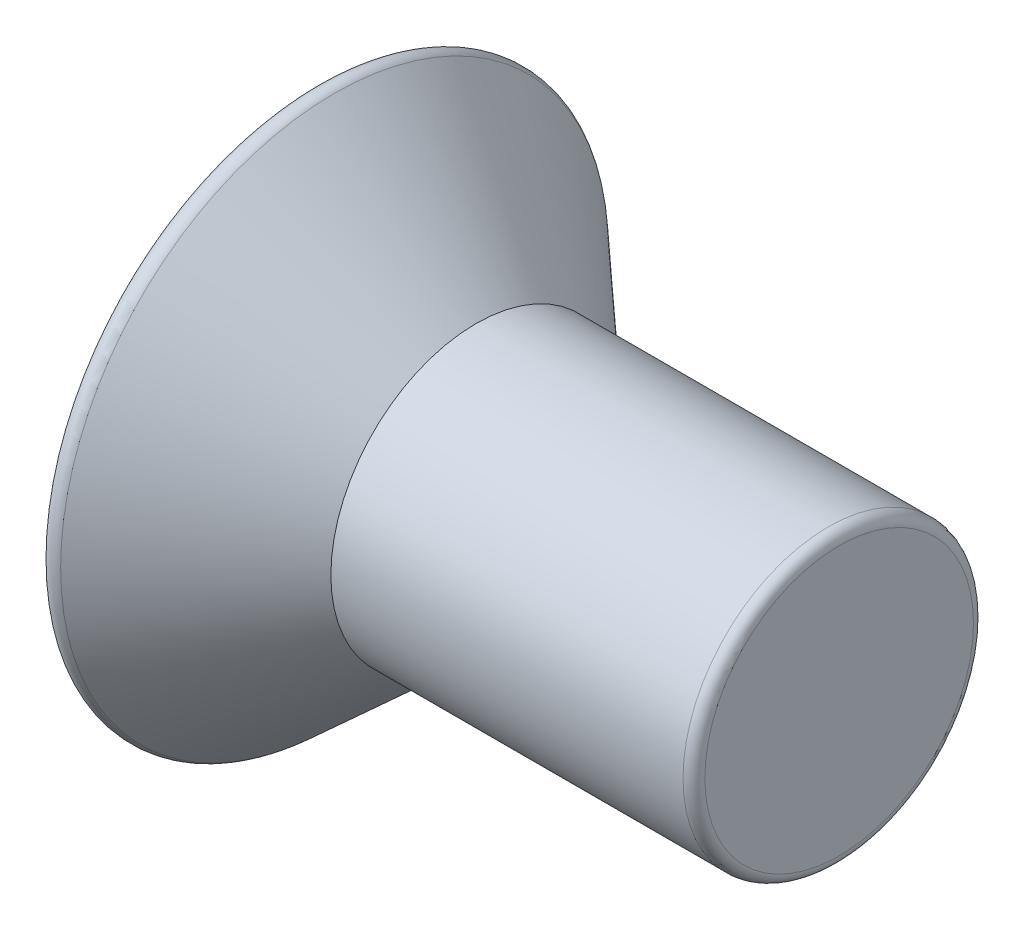
SolidWorks part; units mm, degrees
material "1.0044 (S275JR)"
ref_plane "Ön Düzlem" through (0, 0, 0) normal (0, 0, 1) x (1, 0, 0)
ref_plane "Üst Düzlem" through (0, 0, 0) normal (0, 1, 0) x (1, 0, 0)
ref_plane "Sağ Düzlem" through (0, 0, 0) normal (1, 0, 0) x (0, 0, -1)
sketch "Çizim1" plane through (0, 0, 0) normal (0, 0, 1) x (1, 0, 0)
  line L0 (0, 0) -> (0, 4)
  line L1 (0, 4) -> (-10, 4)
  line L2 (-10, 4) -> (-14.4, 8)
  line L3 (-14.4, 8) -> (-14.4, 0)
  line L4 (-14.4, 0) -> (0, 0)
  dimension "D1" = 4
  dimension "D2" = 10
  dimension "D3" = 8
  dimension "D4" = 4.4
revolve "Döndür1" add sketch "Çizim1" angle 360 about L4
cosmetic thread "Kozmetik Diş Açma1" parameters "D2"=6.619
sketch "Çizim2" plane through (-14.4, 0, 0) normal (-1, 0, 0) x (0, 0, 1)
  line L1 (2.8868, 0) -> (1.4434, 2.5)
  line L2 (1.4434, 2.5) -> (-1.4434, 2.5)
  line L3 (-1.4434, 2.5) -> (-2.8868, 0)
  line L4 (-2.8868, 0) -> (-1.4434, -2.5)
  line L5 (-1.4434, -2.5) -> (1.4434, -2.5)
  line L6 (1.4434, -2.5) -> (2.8868, 0)
  circle A0 centre (0, 0) radius 2.5 construction
  dimension "D1" = 5
extrude "Kes-Ekstrüzyon1" cut sketch "Çizim2" against normal blind 5
fillet "Radyus2" radius 0.3 2 edges at (0, 0, 4) (-14.4, 0, 8)
